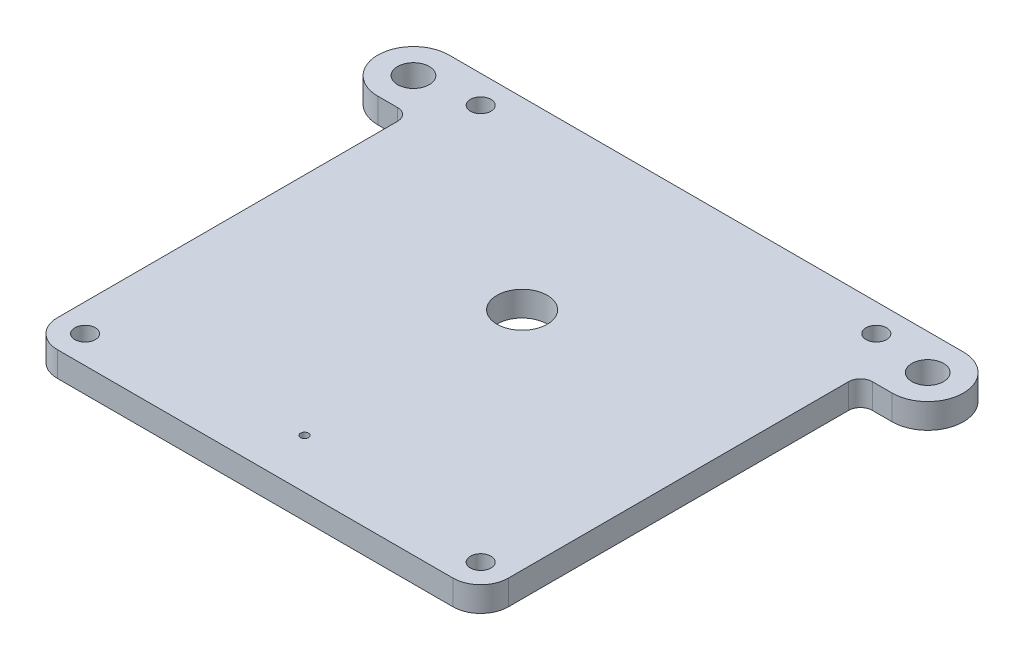
SolidWorks part; units mm, degrees
ref_plane "Front Plane" through (0, 0, 0) normal (0, 0, 1) x (1, 0, 0)
ref_plane "Top Plane" through (0, 0, 0) normal (0, 1, 0) x (1, 0, 0)
ref_plane "Right Plane" through (0, 0, 0) normal (1, 0, 0) x (0, 0, -1)
sketch "Sketch1" plane through (0, 0, 0) normal (0, 1, 0) x (1, 0, 0)
  line L0 (0, 0) -> (0, -101.5278) construction
  line L1 (-65, 0) -> (65, 0)
  line L2 (50, -107) -> (50, -114) construction
  line L3 (50, -7) -> (50, 0) construction
  line L4 (65, -18) -> (60, -18)
  line L5 (57, -21) -> (57, -107)
  line L6 (50, -114) -> (-50, -114)
  line L7 (65, -9) -> (0, -46.5278) construction
  line L8 (-65, -9) -> (0, -46.5278) construction
  line L9 (-50, -7) -> (-50, 0) construction
  line L10 (-50, -107) -> (-50, -114) construction
  line L11 (-57, -21) -> (-57, -107)
  line L12 (-65, -18) -> (-60, -18)
  circle A0 centre (-50, -107) radius 2.6
  circle A1 centre (50, -7) radius 2.6
  arc A2 (-57, -107) -> (-50, -114) centre (-50, -107) ccw
  arc A3 (65, 0) -> (65, -18) centre (65, -9) cw
  arc A4 (60, -18) -> (57, -21) centre (60, -21) ccw
  circle A5 centre (65, -9) radius 4
  arc A6 (57, -107) -> (50, -114) centre (50, -107) cw
  circle A7 centre (50, -107) radius 2.6
  circle A8 centre (0, -46.5278) radius 6.35
  circle A9 centre (0, -101.5278) radius 1
  circle A10 centre (-65, -9) radius 4
  arc A11 (-60, -18) -> (-57, -21) centre (-60, -21) cw
  arc A12 (-65, 0) -> (-65, -18) centre (-65, -9) ccw
  circle A13 centre (-50, -7) radius 2.6
  point P37 (0, -114)
  dimension "D3" = 5.2
  dimension "D4" = 8
  dimension "D6" = 9
  dimension "D7" = 114
  dimension "D9" = 6.35
  dimension "D11" = 2
  dimension "D13" = 7
  dimension "D8" = 3
  dimension "D2" = 57
  dimension "D5" = 65
  dimension "D10" = 120
  dimension "D12" = 55
extrude "Boss-Extrude2" add sketch "Sketch1" along normal blind 6.3
